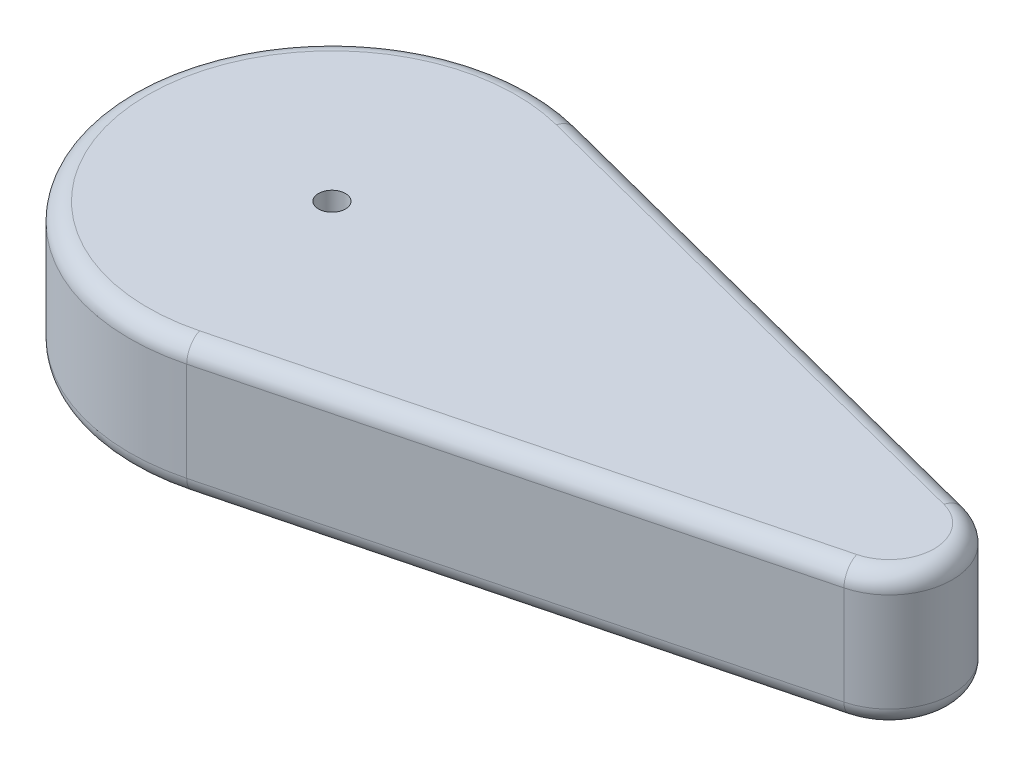
SolidWorks part; units mm, degrees
ref_plane "Front Plane" through (0, 0, 0) normal (0, 0, 1) x (1, 0, 0)
ref_plane "Top Plane" through (0, 0, 0) normal (0, 1, 0) x (1, 0, 0)
ref_plane "Right Plane" through (0, 0, 0) normal (1, 0, 0) x (0, 0, -1)
sketch "Sketch1" plane through (0, 0, 0) normal (0, 1, 0) x (1, 0, 0)
  line L0 (0, 0) -> (62, 0) construction
  line L1 (63.75, -6.7777) -> (5.625, -21.7855)
  line L2 (63.75, 6.7777) -> (5.625, 21.7855)
  circle A0 centre (0, 0) radius 1.5
  circle A1 centre (0, 0) radius 22.5
  circle A2 centre (62, 0) radius 7
  dimension "D1" = 45
  dimension "D2" = 14
  dimension "D4" = 3
  dimension "D3" = 62
extrude "Cam" add sketch "Sketch1" along normal blind 15
fillet "Cam_Fillet_2mm" radius 2 8 edges at (34.6875, 0, -14.2816) (69, 0, 0) (-22.5, 0, 0) (34.6875, 0, 14.2816) (34.6875, 15, -14.2816) (69, 15, 0) (34.6875, 15, 14.2816) (-22.5, 15, 0)
sketch "Sketch2" plane through (0, 0, 0) normal (0, -1, 0) x (1, 0, 0)
  line L1 (0, 4.5) -> (27.5, 4.5)
  line L2 (0, 4.5) -> (0, -4.5)
  line L3 (0, -4.5) -> (27.5, -4.5)
  line L4 (27.5, 4.5) -> (27.5, -4.5)
  circle A0 centre (0, 0) radius 8
  point P7 (0, 0)
  circle M10 centre (0, 0) radius 1.5
  dimension "D3" = 16
  dimension "D1" = 27.5
  dimension "D2" = 9
extrude "Servo_adapter_cut" cut sketch "Sketch2" against normal blind 7 contours L1 A0 L3 L2 M10 | L3 A0 L1 L2 M10 | A0 L3 L4 L1
fillet "Fillet_4.5mm" radius 4 4 edges at (27.5, 3.5, -4.5) (27.5, 3.5, 4.5) (6.6144, 3.5, 4.5) (6.6144, 3.5, -4.5)
